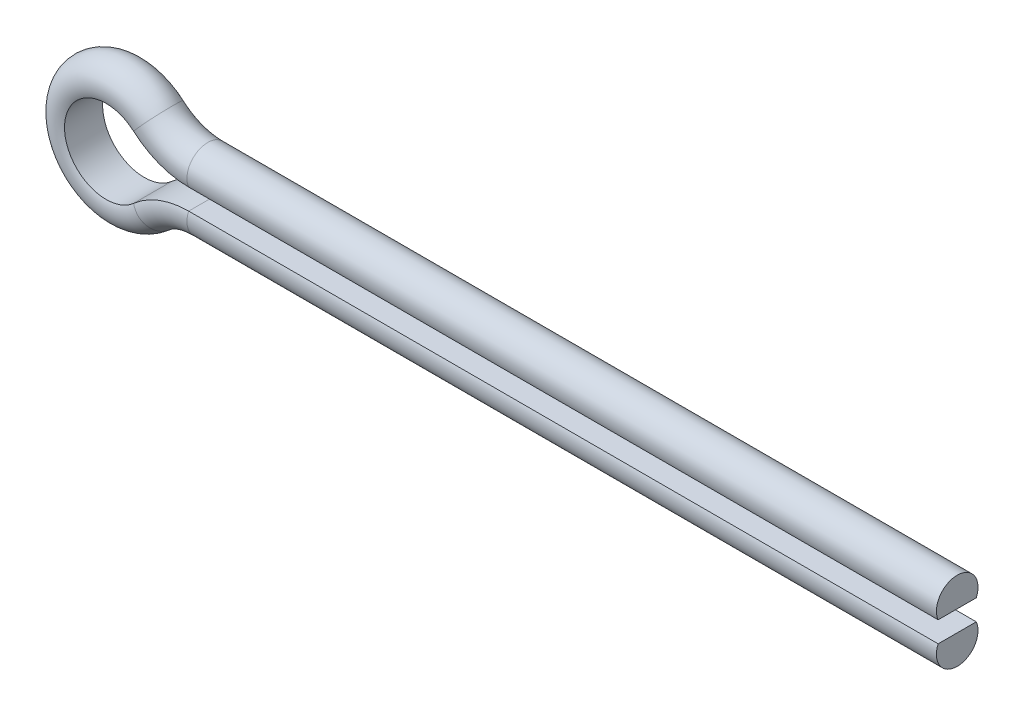
SolidWorks part; units mm, degrees
ref_plane "Front Plane" through (0, 0, 0) normal (0, 0, 1) x (1, 0, 0)
ref_plane "Top Plane" through (0, 0, 0) normal (0, 1, 0) x (1, 0, 0)
ref_plane "Right Plane" through (0, 0, 0) normal (1, 0, 0) x (0, 0, -1)
sketch "Sketch22" plane through (0, 0, 0) normal (0, 0, 1) x (1, 0, 0)
  line L0 (96.0967, 0) -> (6.0182, 0)
  line L1 (96.0967, 2.5) -> (6.0182, 2.5)
  line L2 (-3.9033, 1.25) -> (72.3609, 1.25) construction
  arc A0 (-0.5962, 5) -> (-0.5962, -2.5) centre (-3.9033, 1.25) ccw
  arc A1 (-0.5962, 5) -> (6.0182, 2.5) centre (6.0182, 12.5) ccw
  arc A2 (-0.5962, -2.5) -> (6.0182, 0) centre (6.0182, -10) cw
  point P7 (0, 0)
  dimension "D3" = 100
  dimension "D1" = 10
  dimension "D4" = 5
  dimension "D2" = 2.5
  dimension "D5" = 6.0182
ref_plane "Plane1" through (96.0967, 0, 0) normal (1, 0, 0) x (0, 0, -1)
sketch "Sketch25" plane through (96.0967, 0, 0) normal (1, 0, 0) x (0, 0, -1)
  line L0 (-2.2913, 2.5) -> (2.2913, 2.5)
  line L1 (0, 5) -> (0, 2.5) construction
  line L2 (0, 6.25) -> (0, -3.75) construction
  arc A0 (2.2913, 2.5) -> (-2.2913, 2.5) centre (0, 3.5) ccw
  point P1 (0, 6)
  point P2 (0, 2.5)
  point P5 (0, 2.5)
  point P6 (0, 0)
  dimension "D2" = 2.5
  dimension "D1" = 3.5
sweep "Sweep3" add profiles "Sketch25" path "Sketch22"
